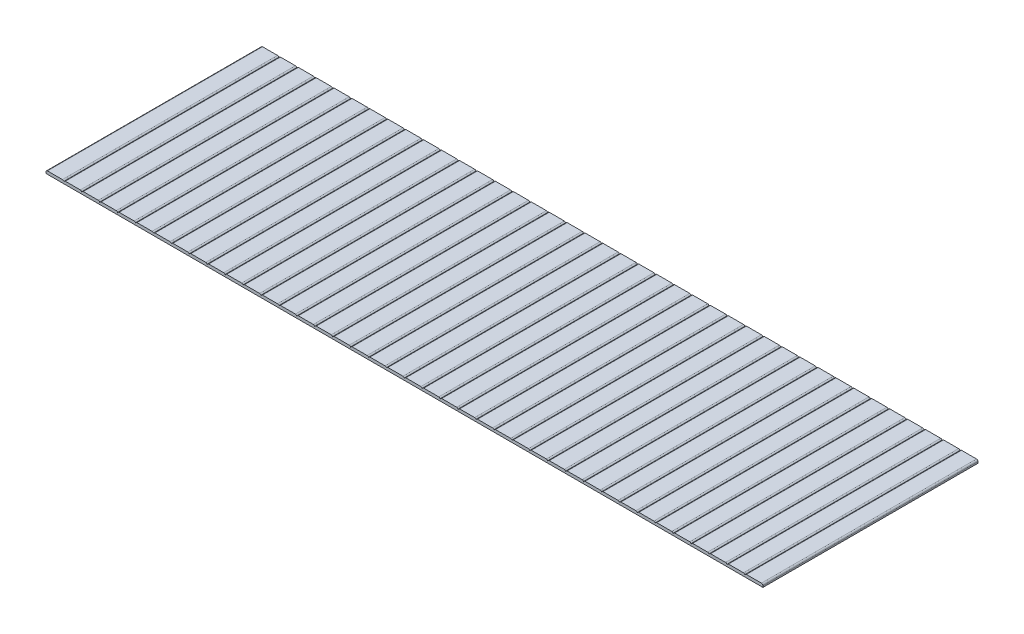
SolidWorks part; units mm, degrees
ref_plane "Front Plane" through (0, 0, 0) normal (0, 0, 1) x (1, 0, 0)
ref_plane "Top Plane" through (0, 0, 0) normal (0, 1, 0) x (1, 0, 0)
ref_plane "Right Plane" through (0, 0, 0) normal (1, 0, 0) x (0, 0, -1)
sketch "bottom floor" plane through (0, 0, 0) normal (0, 1, 0) x (1, 0, 0)
  line L0 (0, 0) -> (-4876.8, 0) construction
  line L1 (-4876.8, -6096) -> (-4876.8, -4927.6) construction
  line L2 (-6096, -6096) -> (-3657.6, -6096)
  line L3 (-6096, -6096) -> (-6096, 6096)
  line L4 (-6096, 6096) -> (-3657.6, 6096)
  line L5 (-3657.6, -6096) -> (-3657.6, 6096)
  line L6 (-6096, -6096) -> (-3657.6, 6096) construction
  line L7 (-6096, 6096) -> (-3657.6, -6096) construction
  line L8 (-5791.2, -5943.6) -> (-3962.4, -5943.6)
  line L9 (-5791.2, -5943.6) -> (-5791.2, -3911.6)
  line L10 (-5791.2, -3911.6) -> (-3962.4, -3911.6)
  line L11 (-3962.4, -5943.6) -> (-3962.4, -3911.6)
  line L12 (-5791.2, -5943.6) -> (-3962.4, -3911.6) construction
  line L13 (-5791.2, -3911.6) -> (-3962.4, -5943.6) construction
  line L14 (-3657.6, -2743.2) -> (-3695.7, -2743.2) construction
  line L15 (-4064, -381) -> (-4064, -406.4) construction
  line L16 (-3733.8, -3657.6) -> (-3657.6, -3657.6)
  line L17 (-3733.8, -3657.6) -> (-3733.8, -1828.8)
  line L18 (-3733.8, -1828.8) -> (-3657.6, -1828.8)
  line L19 (-3657.6, -3657.6) -> (-3657.6, -1828.8)
  line L20 (-3733.8, -3657.6) -> (-3657.6, -1828.8) construction
  line L21 (-3733.8, -1828.8) -> (-3657.6, -3657.6) construction
  line L22 (0, 0) -> (4876.8, 0) construction
  line L23 (-4445, -685.8) -> (-3683, -685.8)
  line L24 (-4445, -685.8) -> (-4445, -76.2)
  line L25 (-4445, -76.2) -> (-3683, -76.2)
  line L26 (-3683, -685.8) -> (-3683, -76.2)
  line L27 (-4445, -685.8) -> (-3683, -76.2) construction
  line L28 (-4445, -76.2) -> (-3683, -685.8) construction
  line L29 (-3657.6, 0) -> (-6096, 0)
  line L30 (-4800.6, -228.6) -> (-4800.6, -635) construction
  line L31 (-5181.6, -1524) -> (-6096, -1524)
  line L32 (-5181.6, -1524) -> (-5181.6, 1524)
  line L33 (-5181.6, 0) -> (-6096, 0)
  line L34 (-6096, -1524) -> (-6096, 1524)
  line L35 (3657.6, 6096) -> (6096, 6096)
  line L36 (3657.6, 6096) -> (3657.6, -6096)
  line L37 (3657.6, -6096) -> (6096, -6096)
  line L38 (6096, 6096) -> (6096, -6096)
  line L39 (3657.6, 6096) -> (6096, -6096) construction
  line L40 (3657.6, -6096) -> (6096, 6096) construction
  line L41 (-4064, -76.2) -> (-4064, -177.8) construction
  line L42 (-4368.8, -635) -> (-3759.2, -635)
  line L43 (-4368.8, -635) -> (-4368.8, -177.8)
  line L44 (-4368.8, -177.8) -> (-3759.2, -177.8)
  line L45 (-3759.2, -635) -> (-3759.2, -177.8)
  line L46 (-4368.8, -635) -> (-3759.2, -177.8) construction
  line L47 (-4368.8, -177.8) -> (-3759.2, -635) construction
  line L48 (6096, 3962.4) -> (6057.9, 3962.4) construction
  line L49 (5791.2, 5105.4) -> (6096, 5105.4) construction
  line L50 (6019.8, 3200.4) -> (6096, 3200.4)
  line L51 (6019.8, 3200.4) -> (6019.8, 4724.4)
  line L52 (6019.8, 4724.4) -> (6096, 4724.4)
  line L53 (6096, 3200.4) -> (6096, 4724.4)
  line L54 (6019.8, 3200.4) -> (6096, 4724.4) construction
  line L55 (6019.8, 4724.4) -> (6096, 3200.4) construction
  line L56 (5486.4, 4800.6) -> (6096, 4800.6)
  line L57 (5486.4, 4800.6) -> (5486.4, 5410.2)
  line L58 (5486.4, 5410.2) -> (6096, 5410.2)
  line L59 (6096, 4800.6) -> (6096, 5410.2)
  line L60 (5486.4, 4800.6) -> (6096, 5410.2) construction
  line L61 (5486.4, 5410.2) -> (6096, 4800.6) construction
  line L62 (5638.8, 4953) -> (5943.6, 4953)
  line L63 (5638.8, 4953) -> (5638.8, 5257.8)
  line L64 (5638.8, 5257.8) -> (5943.6, 5257.8)
  line L65 (5943.6, 4953) -> (5943.6, 5257.8)
  line L66 (5638.8, 4953) -> (5943.6, 5257.8) construction
  line L67 (5638.8, 5257.8) -> (5943.6, 4953) construction
  line L68 (5638.8, 2667) -> (5943.6, 2971.8) construction
  line L69 (5638.8, 2971.8) -> (5943.6, 2667) construction
  line L70 (5486.4, 2514.6) -> (6096, 3124.2) construction
  line L71 (5486.4, 3124.2) -> (6096, 2514.6) construction
  line L72 (5791.2, 2819.4) -> (6096, 2819.4) construction
  line L73 (5943.6, 2971.8) -> (5943.6, 2667)
  line L74 (5638.8, 2667) -> (5943.6, 2667)
  line L75 (5638.8, 2971.8) -> (5638.8, 2667)
  line L76 (5638.8, 2971.8) -> (5943.6, 2971.8)
  line L77 (6096, 3124.2) -> (6096, 2514.6)
  line L78 (5486.4, 2514.6) -> (6096, 2514.6)
  line L79 (5486.4, 3124.2) -> (5486.4, 2514.6)
  line L80 (5486.4, 3124.2) -> (6096, 3124.2)
  line L81 (6019.8, 3200.4) -> (6096, 3200.4)
  line L82 (4876.8, 0) -> (3657.6, 0) construction
  line L83 (3657.6, 2133.6) -> (3657.6, 5791.2)
  line L84 (3657.6, 2133.6) -> (3733.8, 2133.6)
  line L85 (3657.6, 5791.2) -> (3733.8, 5791.2)
  line L86 (3733.8, 2133.6) -> (3733.8, 5791.2)
  line L87 (3733.8, -2133.6) -> (3733.8, -5791.2)
  line L88 (3657.6, -5791.2) -> (3733.8, -5791.2)
  line L89 (3657.6, -2133.6) -> (3733.8, -2133.6)
  line L90 (3657.6, -2133.6) -> (3657.6, -5791.2)
  line L91 (3733.8, 3962.4) -> (6057.9, 3962.4) construction
  line L92 (-5181.6, -1524) -> (-6096, 0) construction
  line L93 (3733.8, -1828.8) -> (3657.6, -1828.8)
  line L94 (3733.8, -1828.8) -> (3733.8, 1828.8)
  line L95 (3733.8, 1828.8) -> (3657.6, 1828.8)
  line L96 (3657.6, -1828.8) -> (3657.6, 1828.8)
  line L97 (3733.8, -1828.8) -> (3657.6, 1828.8) construction
  line L98 (3733.8, 1828.8) -> (3657.6, -1828.8) construction
  line L99 (-5181.6, 0) -> (-6096, -1524) construction
  line L100 (-5105.4, -381) -> (-4495.8, -381)
  line L101 (-5105.4, -381) -> (-5105.4, -76.2)
  line L102 (-5105.4, -76.2) -> (-4495.8, -76.2)
  line L103 (-4495.8, -381) -> (-4495.8, -76.2)
  line L104 (-5105.4, -381) -> (-4495.8, -76.2) construction
  line L105 (-5105.4, -76.2) -> (-4495.8, -381) construction
  line L106 (-6096, -1524) -> (-3657.6, -1524)
  line L107 (-3657.6, -1524) -> (-4304.1784, -2170.5784)
  line L108 (-6096, -1600.2) -> (-6096, -3124.2)
  line L109 (-6096, -1600.2) -> (-5486.4, -1600.2)
  line L110 (-6096, -3124.2) -> (-5486.4, -3124.2)
  line L111 (-5486.4, -1600.2) -> (-5486.4, -3124.2)
  line L112 (-3352.8, 0) -> (-3352.8, -1524)
  line L113 (-3657.6, 0) -> (-609.6, 0)
  line L114 (-3657.6, 0) -> (-3657.6, -1524)
  line L115 (-3657.6, -1524) -> (-609.6, -1524)
  line L116 (-609.6, 0) -> (-609.6, -1524)
  line L117 (-3048, 0) -> (-3048, -1524)
  line L118 (-2743.2, 0) -> (-2743.2, -1524)
  line L119 (-2438.4, 0) -> (-2438.4, -1524)
  line L120 (-2133.6, 0) -> (-2133.6, -1524)
  line L121 (-1828.8, 0) -> (-1828.8, -1524)
  line L122 (-1524, 0) -> (-1524, -1524)
  line L123 (-1219.2, 0) -> (-1219.2, -1524)
  line L124 (-914.4, 0) -> (-914.4, -1524)
  line L125 (5181.6, -6096) -> (5181.6, -2133.6)
  line L126 (3886.2, -6019.8) -> (5105.4, -6019.8)
  line L127 (3886.2, -6019.8) -> (3886.2, -5105.4)
  line L128 (3886.2, -5105.4) -> (5105.4, -5105.4)
  line L129 (5105.4, -6019.8) -> (5105.4, -5105.4)
  line L130 (3886.2, -6019.8) -> (5105.4, -5105.4) construction
  line L131 (3886.2, -5105.4) -> (5105.4, -6019.8) construction
  line L132 (5181.6, -2133.6) -> (6096, -2133.6)
  line L133 (5334, -533.4) -> (5334, -76.2)
  line L134 (4267.2, -1295.4) -> (5486.4, -1295.4)
  line L135 (4267.2, -1295.4) -> (4267.2, 1295.4)
  line L136 (4267.2, 1295.4) -> (5486.4, 1295.4)
  line L137 (5486.4, -1295.4) -> (5486.4, 1295.4)
  line L138 (4267.2, -1295.4) -> (5486.4, 1295.4) construction
  line L139 (4267.2, 1295.4) -> (5486.4, -1295.4) construction
  line L140 (5334, -1143) -> (5943.6, -1143)
  line L141 (5334, -1143) -> (5334, -685.8)
  line L142 (5334, -685.8) -> (5943.6, -685.8)
  line L143 (5943.6, -1143) -> (5943.6, -685.8)
  line L144 (5334, -1143) -> (5943.6, -685.8) construction
  line L145 (5334, -685.8) -> (5943.6, -1143) construction
  line L146 (5334, -76.2) -> (5943.6, -76.2)
  line L147 (5943.6, -533.4) -> (5943.6, -76.2)
  line L148 (5334, -533.4) -> (5943.6, -533.4)
  line L149 (5334, 76.2) -> (5334, 533.4)
  line L150 (5334, 533.4) -> (5943.6, 533.4)
  line L151 (5943.6, 76.2) -> (5943.6, 533.4)
  line L152 (5334, 76.2) -> (5943.6, 76.2)
  line L153 (5334, 685.8) -> (5334, 1143)
  line L154 (5334, 1143) -> (5943.6, 1143)
  line L155 (5943.6, 685.8) -> (5943.6, 1143)
  line L156 (5334, 685.8) -> (5943.6, 685.8)
  line L157 (4876.8, 0) -> (4876.8, -1295.4) construction
  line L158 (4419.6, -685.8) -> (3810, -1143) construction
  line L159 (4419.6, -1143) -> (3810, -685.8) construction
  line L160 (4419.6, 685.8) -> (3810, 685.8)
  line L161 (3810, 685.8) -> (3810, 1143)
  line L162 (4419.6, 1143) -> (3810, 1143)
  line L163 (4419.6, 685.8) -> (4419.6, 1143)
  line L164 (4419.6, 76.2) -> (3810, 76.2)
  line L165 (3810, 76.2) -> (3810, 533.4)
  line L166 (4419.6, 533.4) -> (3810, 533.4)
  line L167 (4419.6, 76.2) -> (4419.6, 533.4)
  line L168 (4419.6, -533.4) -> (3810, -533.4)
  line L169 (3810, -533.4) -> (3810, -76.2)
  line L170 (4419.6, -76.2) -> (3810, -76.2)
  line L171 (3810, -1143) -> (3810, -685.8)
  line L172 (4419.6, -685.8) -> (3810, -685.8)
  line L173 (4419.6, -1143) -> (4419.6, -685.8)
  line L174 (4419.6, -1143) -> (3810, -1143)
  line L175 (4419.6, -533.4) -> (4419.6, -76.2)
  line L176 (-5105.4, 76.2) -> (-4495.8, 381) construction
  line L177 (-5105.4, 381) -> (-4495.8, 76.2) construction
  line L178 (-5181.6, 0) -> (-6096, 1524) construction
  line L179 (-5181.6, 1524) -> (-6096, 0) construction
  line L180 (-4368.8, 177.8) -> (-3759.2, 635) construction
  line L181 (-4368.8, 635) -> (-3759.2, 177.8) construction
  line L182 (-4064, 76.2) -> (-4064, 177.8) construction
  line L183 (-4800.6, 228.6) -> (-4800.6, 635) construction
  line L184 (-4445, 76.2) -> (-3683, 685.8) construction
  line L185 (-4445, 685.8) -> (-3683, 76.2) construction
  line L186 (-3733.8, 1828.8) -> (-3657.6, 3657.6) construction
  line L187 (-3733.8, 3657.6) -> (-3657.6, 1828.8) construction
  line L188 (-4064, 381) -> (-4064, 406.4) construction
  line L189 (-3657.6, 2743.2) -> (-3695.7, 2743.2) construction
  line L190 (-5791.2, 3911.6) -> (-3962.4, 5943.6) construction
  line L191 (-5791.2, 5943.6) -> (-3962.4, 3911.6) construction
  line L192 (-4876.8, 6096) -> (-4876.8, 4927.6) construction
  line L193 (-5486.4, 1600.2) -> (-5486.4, 3124.2)
  line L194 (-6096, 3124.2) -> (-5486.4, 3124.2)
  line L195 (-6096, 1600.2) -> (-5486.4, 1600.2)
  line L196 (-6096, 1600.2) -> (-6096, 3124.2)
  line L197 (-3657.6, 1524) -> (-4304.1784, 2170.5784)
  line L198 (-6096, 1524) -> (-3657.6, 1524)
  line L199 (-4495.8, 381) -> (-4495.8, 76.2)
  line L200 (-5105.4, 76.2) -> (-4495.8, 76.2)
  line L201 (-5105.4, 381) -> (-5105.4, 76.2)
  line L202 (-5105.4, 381) -> (-4495.8, 381)
  line L203 (-3759.2, 635) -> (-3759.2, 177.8)
  line L204 (-4368.8, 177.8) -> (-3759.2, 177.8)
  line L205 (-4368.8, 635) -> (-4368.8, 177.8)
  line L206 (-4368.8, 635) -> (-3759.2, 635)
  line L207 (-5181.6, 1524) -> (-6096, 1524)
  line L208 (-3683, 685.8) -> (-3683, 76.2)
  line L209 (-4445, 76.2) -> (-3683, 76.2)
  line L210 (-4445, 685.8) -> (-4445, 76.2)
  line L211 (-4445, 685.8) -> (-3683, 685.8)
  line L212 (-3657.6, 3657.6) -> (-3657.6, 1828.8)
  line L213 (-3733.8, 1828.8) -> (-3657.6, 1828.8)
  line L214 (-3733.8, 3657.6) -> (-3733.8, 1828.8)
  line L215 (-3733.8, 3657.6) -> (-3657.6, 3657.6)
  line L216 (-3962.4, 5943.6) -> (-3962.4, 3911.6)
  line L217 (-5791.2, 3911.6) -> (-3962.4, 3911.6)
  line L218 (-5791.2, 5943.6) -> (-5791.2, 3911.6)
  line L219 (-5791.2, 5943.6) -> (-3962.4, 5943.6)
  line L220 (-6096, 6096) -> (-3657.6, 6096)
  circle A0 centre (-4800.6, -635) radius 254
  circle A1 centre (-4064, -127) radius 25.4
  arc A2 (-4304.1784, -2170.5784) -> (-4572, -1524) centre (-3657.6, -1524) cw
  arc A3 (-4304.1784, 2170.5784) -> (-4572, 1524) centre (-3657.6, 1524) ccw
  circle A4 centre (-4064, 127) radius 25.4
  circle A5 centre (-4800.6, 635) radius 254
  point P7 (-4876.8, -4927.6)
  point P20 (-4064, -381)
  point P26 (-3657.6, 6019.8)
  point P27 (4876.8, 0)
  point P30 (-5638.8, -762)
  point P31 (-4800.6, -228.6)
  point P48 (5791.2, 5105.4)
  point P53 (5791.2, 5105.4)
  point P81 (3695.7, 0)
  point P111 (4495.8, -5562.6)
  point P139 (5638.8, -914.4)
  point P173 (4114.8, -914.4)
  point P216 (-5638.8, 762)
  point P217 (-3657.6, -6019.8)
  dimension "D31" = 508
  dimension "D37" = 50.8
  dimension "D1" = 2438.4
  dimension "D2" = 12192
  dimension "D3" = 1828.8
  dimension "D4" = 2032
  dimension "D5" = 152.4
  dimension "D6" = 76.2
  dimension "D7" = 1828.8
  dimension "D8" = 1828.8
  dimension "D9" = 762
  dimension "D10" = 609.6
  dimension "D11" = 50.8
  dimension "D12" = 304.8
  dimension "D13" = 2438.4
  dimension "D14" = 12192
  dimension "D15" = 12192
  dimension "D16" = 76.2
  dimension "D17" = 1524
  dimension "D18" = 76.2
  dimension "D19" = 609.6
  dimension "D20" = 609.6
  dimension "D21" = 304.8
  dimension "D22" = 304.8
  dimension "D23" = 76.2
  dimension "D24" = 914.4
  dimension "D25" = 76.2
  dimension "D26" = 3657.6
  dimension "D27" = 3657.6
  dimension "D28" = 1524
  dimension "D29" = 609.6
  dimension "D30" = 304.8
  dimension "D32" = 76.2
  dimension "D33" = 76.2
  dimension "D34" = 50.8
  dimension "D35" = 609.6
  dimension "D36" = 457.2
  dimension "D38" = 914.4
  dimension "D39" = 45
  dimension "D40" = 609.6
  dimension "D41" = 1524
  dimension "D42" = 76.2
  dimension "D43" = 3048
  dimension "D44" = 1524
  dimension "D45" = 304.8
  dimension "D47" = 1219.2
  dimension "D48" = 914.4
  dimension "D49" = 76.2
  dimension "D50" = 3962.4
  dimension "D51" = 914.4
  dimension "D52" = 76.2
  dimension "D53" = 609.6
  dimension "D54" = 457.2
  dimension "D55" = 152.4
  dimension "D56" = 152.4
  dimension "D58" = 152.4
  dimension "D59" = 304.8
  dimension "D60" = 76.2
  dimension "D61" = 2590.8
  dimension "D62" = 1219.2
  dimension "D63" = 76.2
  dimension "D46" = 9
  dimension "D57" = 4
ref_plane "Plane1" through (0, 2895.6, 0) normal (0, 1, 0) x (1, 0, 0)
sketch "top floor" plane through (0, 2895.6, 0) normal (0, 1, 0) x (1, 0, 0)
  line L0 (0, 0) -> (0, 4876.8) construction
  line L1 (-1524, 3657.6) -> (-1524, 3581.4) construction
  line L2 (-6096, 3657.6) -> (6096, 3657.6)
  line L3 (-6096, 3657.6) -> (-6096, 6096)
  line L4 (-6096, 6096) -> (6096, 6096)
  line L5 (6096, 3657.6) -> (6096, 6096)
  line L6 (-6096, 3657.6) -> (6096, 6096) construction
  line L7 (-6096, 6096) -> (6096, 3657.6) construction
  line L8 (1524, 3657.6) -> (1524, 3581.4) construction
  line L9 (-3048, 3505.2) -> (0, 3505.2)
  line L10 (-3048, 3505.2) -> (-3048, 3657.6)
  line L11 (-3048, 3657.6) -> (0, 3657.6)
  line L12 (0, 3505.2) -> (0, 3657.6)
  line L13 (-3048, 3505.2) -> (0, 3657.6) construction
  line L14 (-3048, 3657.6) -> (0, 3505.2) construction
  line L15 (-5461, 4876.8) -> (-6096, 4876.8) construction
  line L16 (3048, 3505.2) -> (0, 3505.2)
  line L17 (3048, 3505.2) -> (3048, 3657.6)
  line L18 (3048, 3657.6) -> (0, 3657.6)
  line L19 (0, 3505.2) -> (0, 3657.6)
  line L20 (3048, 3505.2) -> (0, 3657.6) construction
  line L21 (3048, 3657.6) -> (0, 3505.2) construction
  line L22 (-5943.6, 5892.8) -> (-4978.4, 5892.8)
  line L23 (-5943.6, 5892.8) -> (-5943.6, 3860.8)
  line L24 (-5943.6, 3860.8) -> (-4978.4, 3860.8)
  line L25 (-4978.4, 5892.8) -> (-4978.4, 3860.8)
  line L26 (-5943.6, 5892.8) -> (-4978.4, 3860.8) construction
  line L27 (-5943.6, 3860.8) -> (-4978.4, 5892.8) construction
  line L28 (-3657.6, 3657.6) -> (-3657.6, 6096)
  line L29 (-3657.6, -6096) -> (-3657.6, 6096) construction
  line L30 (-3657.6, 3657.6) -> (-3011.0216, 4304.1784)
  line L31 (-3657.6, -1524) -> (-6096, -1524)
  line L32 (-4267.2, 4572) -> (-3657.6, 4572)
  line L33 (-4267.2, 4572) -> (-4267.2, 6096)
  line L34 (-4267.2, 6096) -> (-3657.6, 6096)
  line L35 (-3657.6, 4572) -> (-3657.6, 6096)
  line L36 (-4267.2, 4572) -> (-3657.6, 6096) construction
  line L37 (-4267.2, 6096) -> (-3657.6, 4572) construction
  line L38 (-6096, -1524) -> (-6096, 3657.6)
  line L39 (-3657.6, 0) -> (3657.6, 0)
  line L40 (3657.6, 0) -> (6096, 0)
  line L41 (6096, 6096) -> (6096, -6096) construction
  line L42 (6096, 0) -> (6096, 3657.6)
  line L43 (-3657.6, 0) -> (-3657.6, -1524)
  line L44 (3657.6, 6096) -> (3657.6, 3657.6)
  line L45 (3657.6, 6096) -> (3657.6, -6096) construction
  line L46 (5943.6, 3860.8) -> (4978.4, 3860.8)
  line L47 (4978.4, 5892.8) -> (4978.4, 3860.8)
  line L48 (5943.6, 5892.8) -> (4978.4, 5892.8)
  line L49 (5943.6, 5892.8) -> (5943.6, 3860.8)
  line L50 (4267.2, 4572) -> (4267.2, 6096)
  line L51 (4267.2, 4572) -> (3657.6, 4572)
  line L52 (3657.6, 3657.6) -> (3011.0216, 4304.1784)
  line L53 (-1219.2, 5410.2) -> (0, 5410.2)
  line L54 (-2438.4, 5410.2) -> (-1219.2, 5410.2)
  line L55 (-2438.4, 5410.2) -> (-2438.4, 6019.8)
  line L56 (-2438.4, 6019.8) -> (-1219.2, 6019.8)
  line L57 (-1219.2, 5410.2) -> (-1219.2, 6019.8)
  line L58 (-2438.4, 5410.2) -> (-1219.2, 6019.8) construction
  line L59 (-2438.4, 6019.8) -> (-1219.2, 5410.2) construction
  line L60 (-1219.2, 5410.2) -> (-1219.2, 6019.8)
  line L61 (-1219.2, 6019.8) -> (0, 6019.8)
  line L62 (0, 5410.2) -> (0, 6019.8)
  line L63 (-1219.2, 5410.2) -> (0, 6019.8) construction
  line L64 (-1219.2, 6019.8) -> (0, 5410.2) construction
  line L65 (0, 5410.2) -> (1219.2, 5410.2)
  line L66 (0, 5410.2) -> (0, 6019.8)
  line L67 (0, 6019.8) -> (1219.2, 6019.8)
  line L68 (1219.2, 5410.2) -> (1219.2, 6019.8)
  line L69 (0, 5410.2) -> (1219.2, 6019.8) construction
  line L70 (0, 6019.8) -> (1219.2, 5410.2) construction
  line L71 (1219.2, 5410.2) -> (2438.4, 5410.2)
  line L72 (1219.2, 5410.2) -> (1219.2, 6019.8)
  line L73 (1219.2, 6019.8) -> (2438.4, 6019.8)
  line L74 (2438.4, 5410.2) -> (2438.4, 6019.8)
  line L75 (1219.2, 5410.2) -> (2438.4, 6019.8) construction
  line L76 (1219.2, 6019.8) -> (2438.4, 5410.2) construction
  line L77 (-2438.4, 5715) -> (-1828.8, 5715) construction
  line L78 (-1828.8, 5715) -> (-1219.2, 5715) construction
  line L79 (-1143, 5486.4) -> (-685.8, 5486.4)
  line L80 (-2362.2, 5486.4) -> (-1905, 5486.4)
  line L81 (-2362.2, 5486.4) -> (-2362.2, 5943.6)
  line L82 (-2362.2, 5943.6) -> (-1905, 5943.6)
  line L83 (-1905, 5486.4) -> (-1905, 5943.6)
  line L84 (-2362.2, 5486.4) -> (-1905, 5943.6) construction
  line L85 (-2362.2, 5943.6) -> (-1905, 5486.4) construction
  line L86 (-1295.4, 5486.4) -> (-1752.6, 5486.4)
  line L87 (-1295.4, 5486.4) -> (-1295.4, 5943.6)
  line L88 (-1295.4, 5943.6) -> (-1752.6, 5943.6)
  line L89 (-1752.6, 5486.4) -> (-1752.6, 5943.6)
  line L90 (-1295.4, 5486.4) -> (-1752.6, 5943.6) construction
  line L91 (-1295.4, 5943.6) -> (-1752.6, 5486.4) construction
  line L92 (-1143, 5486.4) -> (-1143, 5943.6)
  line L93 (-1143, 5943.6) -> (-685.8, 5943.6)
  line L94 (-685.8, 5486.4) -> (-685.8, 5943.6)
  line L95 (-76.2, 5486.4) -> (-533.4, 5486.4)
  line L96 (-76.2, 5486.4) -> (-76.2, 5943.6)
  line L97 (-76.2, 5943.6) -> (-533.4, 5943.6)
  line L98 (-533.4, 5486.4) -> (-533.4, 5943.6)
  line L99 (-1143, 5486.4) -> (-685.8, 5943.6) construction
  line L100 (-1143, 5943.6) -> (-685.8, 5486.4) construction
  line L101 (-76.2, 5486.4) -> (-533.4, 5943.6) construction
  line L102 (-76.2, 5943.6) -> (-533.4, 5486.4) construction
  line L103 (76.2, 5486.4) -> (533.4, 5486.4)
  line L104 (76.2, 5486.4) -> (76.2, 5943.6)
  line L105 (76.2, 5943.6) -> (533.4, 5943.6)
  line L106 (533.4, 5486.4) -> (533.4, 5943.6)
  line L107 (1143, 5486.4) -> (685.8, 5486.4)
  line L108 (1143, 5486.4) -> (1143, 5943.6)
  line L109 (1143, 5943.6) -> (685.8, 5943.6)
  line L110 (685.8, 5486.4) -> (685.8, 5943.6)
  line L111 (76.2, 5486.4) -> (533.4, 5943.6) construction
  line L112 (76.2, 5943.6) -> (533.4, 5486.4) construction
  line L113 (1143, 5486.4) -> (685.8, 5943.6) construction
  line L114 (1143, 5943.6) -> (685.8, 5486.4) construction
  line L115 (1295.4, 5486.4) -> (1752.6, 5486.4)
  line L116 (1295.4, 5486.4) -> (1295.4, 5943.6)
  line L117 (1295.4, 5943.6) -> (1752.6, 5943.6)
  line L118 (1752.6, 5486.4) -> (1752.6, 5943.6)
  line L119 (2362.2, 5486.4) -> (1905, 5486.4)
  line L120 (2362.2, 5486.4) -> (2362.2, 5943.6)
  line L121 (2362.2, 5943.6) -> (1905, 5943.6)
  line L122 (1905, 5486.4) -> (1905, 5943.6)
  line L123 (1295.4, 5486.4) -> (1752.6, 5943.6) construction
  line L124 (1295.4, 5943.6) -> (1752.6, 5486.4) construction
  line L125 (2362.2, 5486.4) -> (1905, 5943.6) construction
  line L126 (2362.2, 5943.6) -> (1905, 5486.4) construction
  line L127 (-1295.4, 5486.4) -> (-1143, 5486.4) construction
  arc A0 (-3011.0216, 4304.1784) -> (-3657.6, 4572) centre (-3657.6, 3657.6) ccw
  arc A1 (3011.0216, 4304.1784) -> (3657.6, 4572) centre (3657.6, 3657.6) cw
  point P16 (-5461, 4876.8)
  point P33 (-3962.4, 5334)
  point P67 (-2133.6, 5715)
  point P88 (-1524, 5715)
  point P94 (-914.4, 5715)
  point P99 (-304.8, 5715)
  point P104 (304.8, 5715)
  point P109 (914.4, 5715)
  point P114 (1524, 5715)
  point P119 (2133.6, 5715)
  dimension "D1" = 2438.4
  dimension "D2" = 3048
  dimension "D3" = 3048
  dimension "D4" = 152.4
  dimension "D5" = 965.2
  dimension "D6" = 2032
  dimension "D7" = 152.4
  dimension "D8" = 914.4
  dimension "D9" = 45
  dimension "D10" = 609.6
  dimension "D11" = 1524
  dimension "D12" = 1219.2
  dimension "D13" = 609.6
  dimension "D15" = 457.2
  dimension "D17" = 2438.4
  dimension "D18" = 76.2
  dimension "D19" = 76.2
  dimension "D14" = 4
  dimension "D16" = 4
ref_plane "Plane2" through (0, 0, 6019.8) normal (0, 0, 1) x (1, 0, 0)
ref_plane "Plane3" through (0, 0, -6096) normal (0, 0, 1) x (1, 0, 0)
sketch "Sketch1" plane through (0, 0, 0) normal (0, 0, 1) x (1, 0, 0)
  line L0 (6096, 2895.6) -> (5791.2, 2895.6)
  line L1 (6096, 2895.6) -> (6096, 2921)
  line L2 (5791.2, 2895.6) -> (5791.2, 2921)
  line L3 (6070.6, 2946.4) -> (5816.6, 2946.4)
  line L6 (3657.6, 2895.6) -> (6096, 2895.6) construction
  arc A0 (6096, 2921) -> (6070.6, 2946.4) centre (6070.6, 2921) ccw
  arc A1 (5791.2, 2921) -> (5816.6, 2946.4) centre (5816.6, 2921) cw
  point P11 (6096, 2946.4)
  point P14 (5791.2, 2946.4)
  dimension "D3" = 25.4
  dimension "D1" = 50.8
  dimension "D2" = 304.8
  dimension "D4" = 0
extrude "Boss-Extrude1" add sketch "Sketch1" against normal blind 3657.6
pattern_linear "LPattern1" count 1 spacing 2.54 along (1, 0, 0) count 40 spacing 304.8 along (-1, 0, 0) of "Boss-Extrude1"
